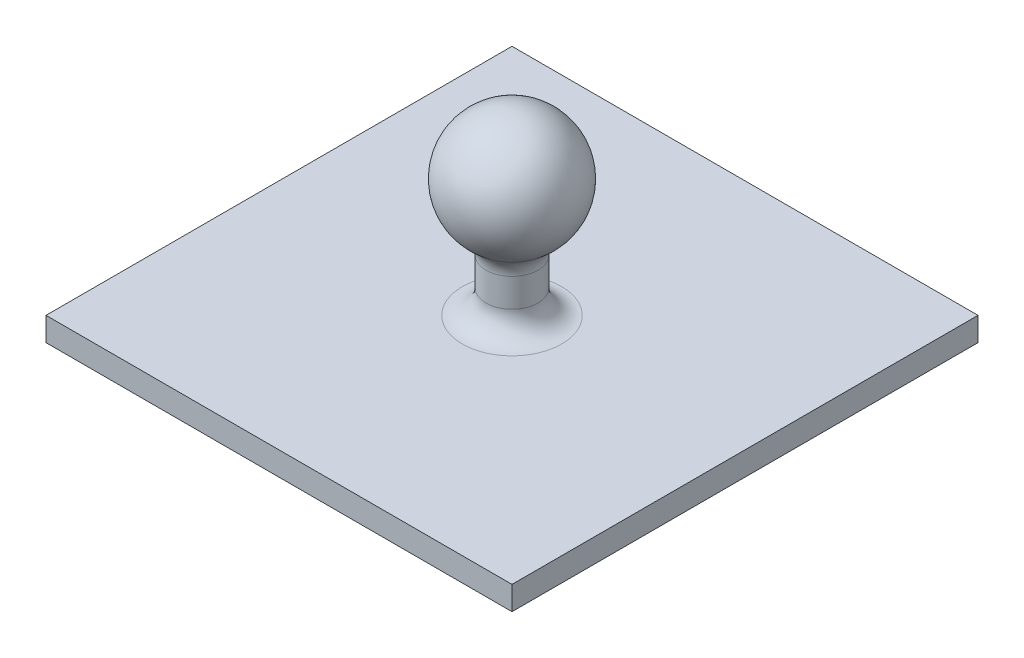
SolidWorks part; units mm, degrees
other "Markup1"
sketch "Sketch7" plane through (50.8, 43.18, 0) normal (0.5774, 0.5773, 0.5774) x (0.7071, 0, -0.7071)
material "Chrome Stainless Steel"
ref_plane "Front Plane" through (0, 0, 0) normal (0, 0, 1) x (1, 0, 0)
ref_plane "Top Plane" through (0, 0, 0) normal (0, 1, 0) x (1, 0, 0)
ref_plane "Right Plane" through (0, 0, 0) normal (1, 0, 0) x (0, 0, -1)
sketch "Sketch2" plane through (0, 0, 0) normal (0, 1, 0) x (1, 0, 0)
  line L0 (0, 100) -> (100, 0) construction
  line L1 (0, 0) -> (100, 0)
  line L2 (0, 0) -> (0, 100)
  line L3 (0, 100) -> (100, 100)
  line L4 (100, 0) -> (100, 100)
  point P8 (50, 50)
  dimension "D1" = 100
  dimension "D2" = 100
extrude "Boss-Extrude1" add sketch "Sketch2" along normal blind 5.08
sketch "Sketch3" plane through (0, 5.08, 0) normal (0, 1, 0) x (1, 0, 0)
  circle A0 centre (50, 50) radius 5.588
  dimension "D3" = 11.176
extrude "Boss-Extrude2" add sketch "Sketch3" along normal blind 25.4
sketch "Sketch6" plane through (0, 30.48, 0) normal (0, 1, 0) x (1, 0, 0)
  line L0 (50, 62.7) -> (50, 37.3)
  arc A0 (50, 37.3) -> (50, 62.7) centre (50, 50) ccw
  dimension "D1" = 25.4
revolve "Revolve1" add sketch "Sketch6" angle 360 about L0
fillet "Fillet1" radius 5.08 2 edges at (50, 19.0754, -44.412) (50, 5.08, -55.588)
sketch "Sketch8" plane through (0, 5.08, 0) normal (0, 1, 0) x (1, 0, 0)
